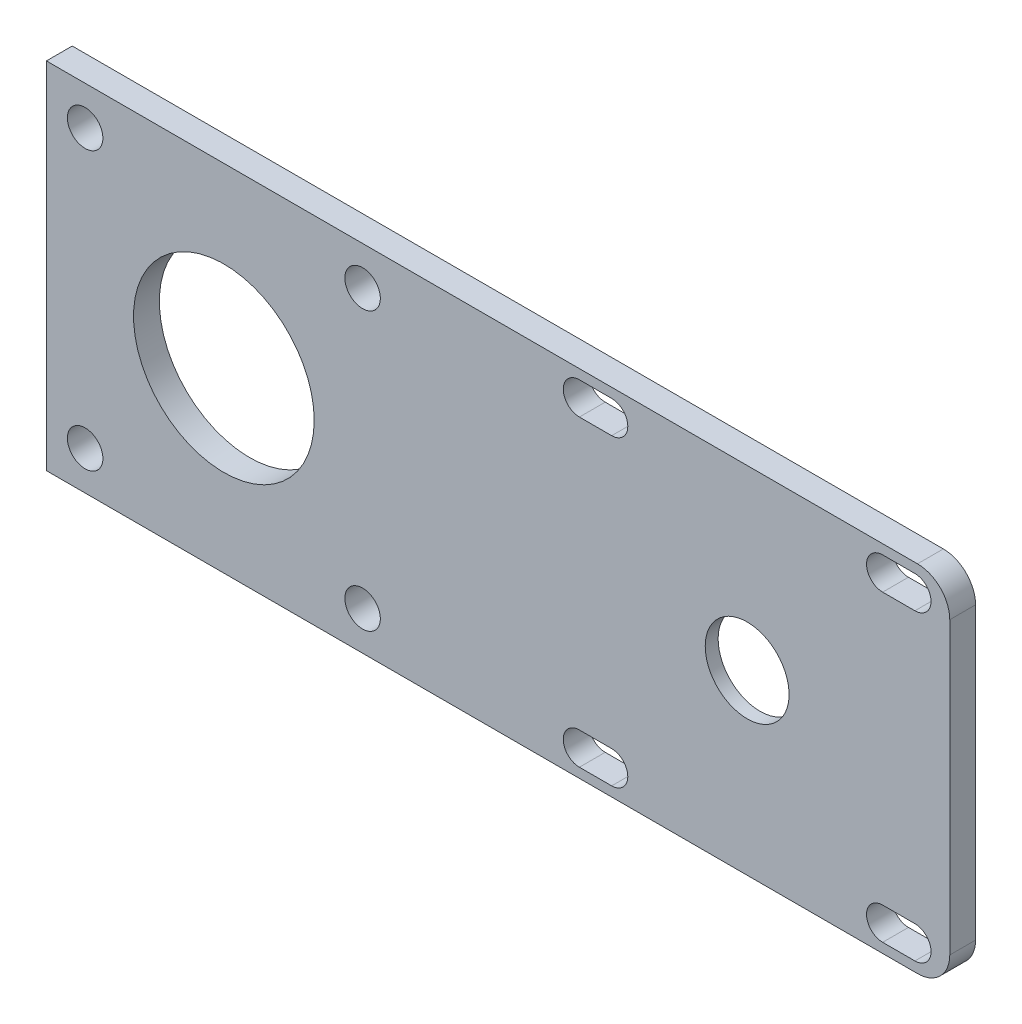
SolidWorks part; units mm, degrees
ref_plane "Piano frontale" through (0, 0, 0) normal (0, 0, 1) x (1, 0, 0)
ref_plane "Piano superiore" through (0, 0, 0) normal (0, 1, 0) x (1, 0, 0)
ref_plane "Piano destro" through (0, 0, 0) normal (1, 0, 0) x (0, 0, -1)
sketch "Schizzo1" plane through (0, 0, 0) normal (0, 0, 1) x (1, 0, 0)
  line L1 (0, 0) -> (140, 0)
  line L2 (0, 0) -> (0, 55)
  line L3 (0, 55) -> (140, 55)
  line L4 (140, 0) -> (140, 55)
  dimension "D1" = 55
  dimension "D2" = 140
extrude "Estrusione-Estrusione1" add sketch "Schizzo1" against normal blind 4
sketch "Schizzo2" plane through (0, 0, 0) normal (0, 0, 1) x (1, 0, 0)
  line L0 (0, 0) -> (0, 69.6041) construction
  line L1 (27.5, 0) -> (27.5, 69.6041) construction
  line L2 (0, 0) -> (60.1033, 0) construction
  line L3 (0, 0) -> (140, 0) construction
  line L4 (0, 27.5) -> (60.1033, 27.5) construction
  line L5 (6, 0) -> (6, 69.6041) construction
  line L6 (0, 6) -> (60.1033, 6) construction
  circle A0 centre (27.5, 27.5) radius 14
  circle A1 centre (6, 6) radius 2.75
  circle A2 centre (49, 6) radius 2.75
  circle A3 centre (49, 49) radius 2.75
  circle A4 centre (6, 49) radius 2.75
  dimension "D3" = 28
  dimension "D6" = 5.5
  dimension "D7" = 6
  dimension "D1" = 27.5
  dimension "D2" = 27.5
  dimension "D4" = 6
  dimension "D5" = 6
extrude "Taglio-Estrusione1" cut sketch "Schizzo2" against normal through all
fillet "Raccordo1" radius 5 2 edges at (140, 0, -2) (140, 55, -2)
sketch "Schizzo3" plane through (0, 0, -4) normal (0, 0, -1) x (-1, 0, 0)
  line L0 (-140, 25.5567) -> (-140, 74.1384) construction
  line L1 (-140, 5) -> (-140, 50) construction
  line L2 (-80.1, 25.5567) -> (-80.1, 74.1384) construction
  line L3 (-137.1, 25.5567) -> (-137.1, 74.1384) construction
  line L4 (-80.1, 27.5) -> (-137.1, 27.5) construction
  line L5 (-134.6, 51) -> (-129.6, 51) construction
  line L6 (-108.6, 27.5) -> (-108.6, 59.8878) construction
  line L8 (-132.1, 27.5) -> (-132.1, 64.4221) construction
  line L9 (-80.1, 51) -> (-137.1, 51) construction
  line L10 (-80.1, 4) -> (-137.1, 4) construction
  line L11 (-132.1, 27.5) -> (-132.1, 74.1384) construction
  line L13 (-108.6, 27.5) -> (-108.6, 74.1384) construction
  line L14 (-108.6, 55) -> (-145.2784, 55) construction
  line L15 (-135, 55) -> (0, 55) construction
  line L16 (-116.2061, 0) -> (-154.4249, 0) construction
  line L17 (0, 0) -> (-135, 0) construction
  line L18 (-134.6, 53.5) -> (-129.6, 53.5)
  line L19 (-134.6, 48.5) -> (-129.6, 48.5)
  line L20 (-82.6, 51) -> (-87.6, 51) construction
  line L21 (-82.6, 51) -> (-87.6, 51) construction
  line L22 (-82.6, 53.5) -> (-87.6, 53.5)
  line L23 (-82.6, 48.5) -> (-87.6, 48.5)
  line L24 (-134.6, 4) -> (-129.6, 4) construction
  line L25 (-134.6, 1.5) -> (-129.6, 1.5)
  line L26 (-134.6, 6.5) -> (-129.6, 6.5)
  line L27 (-82.6, 4) -> (-87.6, 4) construction
  line L28 (-82.6, 1.5) -> (-87.6, 1.5)
  line L29 (-82.6, 6.5) -> (-87.6, 6.5)
  arc A0 (-82.6, 53.5) -> (-82.6, 48.5) centre (-82.6, 51) cw
  arc A1 (-87.6, 48.5) -> (-87.6, 53.5) centre (-87.6, 51) cw
  arc A2 (-134.6, 1.5) -> (-134.6, 6.5) centre (-134.6, 4) cw
  arc A3 (-129.6, 6.5) -> (-129.6, 1.5) centre (-129.6, 4) cw
  arc A4 (-134.6, 53.5) -> (-134.6, 48.5) centre (-134.6, 51) ccw
  circle A5 centre (-108.6, 27.5) radius 6.5
  arc A6 (-129.6, 48.5) -> (-129.6, 53.5) centre (-129.6, 51) ccw
  arc A7 (-82.6, 1.5) -> (-82.6, 6.5) centre (-82.6, 4) ccw
  arc A8 (-87.6, 6.5) -> (-87.6, 1.5) centre (-87.6, 4) ccw
  point P20 (-85.1, 51)
  point P33 (-132.1, 4)
  point P45 (-132.1, 51)
  point P58 (-85.1, 4)
  dimension "D10" = 5
  dimension "D11" = 13
  dimension "D12" = 5
  dimension "D3" = 23.5
  dimension "D1" = 59.9
  dimension "D2" = 57
  dimension "D5" = 23.5
  dimension "D6" = 23.5
extrude "Taglio-Estrusione2" cut sketch "Schizzo3" against normal through all
sketch "Schizzo4" plane through (0, 0, -4) normal (0, 0, -1) x (-1, 0, 0)
  line L1 (-88.6, 9) -> (-128.6, 9)
  line L2 (-83.6, 14) -> (-83.6, 41)
  line L3 (-88.6, 46) -> (-128.6, 46)
  line L4 (-133.6, 14) -> (-133.6, 41)
  line L5 (-83.6, 9) -> (-133.6, 46) construction
  line L6 (-83.6, 46) -> (-133.6, 9) construction
  arc A0 (-88.6, 46) -> (-83.6, 41) centre (-88.6, 41) cw
  arc A1 (-83.6, 14) -> (-88.6, 9) centre (-88.6, 14) cw
  arc A2 (-128.6, 9) -> (-133.6, 14) centre (-128.6, 14) cw
  arc A3 (-133.6, 41) -> (-128.6, 46) centre (-128.6, 41) cw
  point P0 (-108.6, 27.5)
  dimension "D1" = 50
  dimension "D3" = 5
  dimension "D2" = 37
extrude "Taglio-Estrusione3" cut sketch "Schizzo4" against normal blind 2
